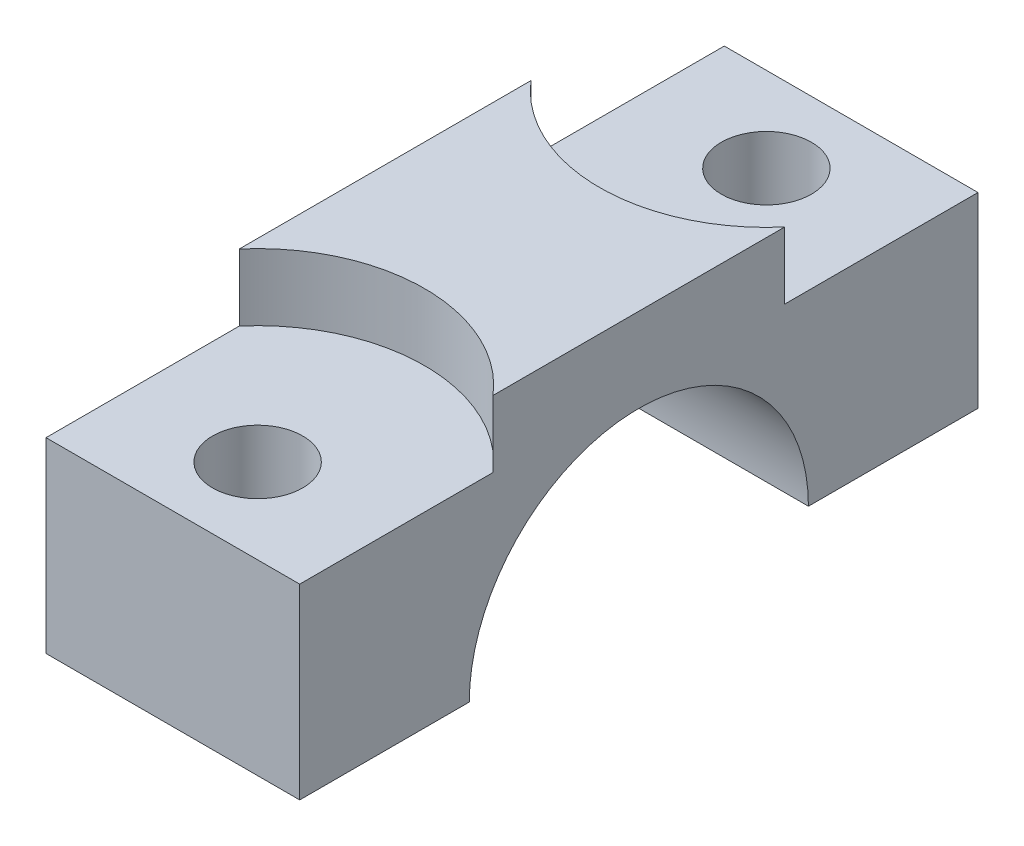
SolidWorks part; units mm, degrees
ref_plane "Front Plane" through (0, 0, 0) normal (0, 0, 1) x (1, 0, 0)
ref_plane "Top Plane" through (0, 0, 0) normal (0, 1, 0) x (1, 0, 0)
ref_plane "Right Plane" through (0, 0, 0) normal (1, 0, 0) x (0, 0, -1)
sketch "Sketch1" plane through (0, 0, 0) normal (1, 0, 0) x (0, 0, -1)
  line L0 (12.7, 0) -> (25.4, 0)
  line L1 (-25.4, 19) -> (25.4, 19)
  line L2 (-25.4, 19) -> (-25.4, 0)
  line L3 (-25.4, 0) -> (-12.7, 0)
  line L4 (25.4, 19) -> (25.4, 0)
  arc A0 (-12.7, 0) -> (12.7, 0) centre (0, 0) cw
  point P10 (0, 19)
  dimension "D3" = 12.7
  dimension "D1" = 50.8
  dimension "D2" = 19
extrude "Boss-Extrude1" add sketch "Sketch1" along normal mid plane 19
sketch "Sketch2" plane through (0, 0, 0) normal (0, -1, 0) x (1, 0, 0)
  line L0 (-9.5, 19.05) -> (9.5, 19.05) construction
  line L1 (-9.5, 25.4) -> (-9.5, 12.7) construction
  line L2 (9.5, 25.4) -> (9.5, 12.7) construction
  line L3 (-9.5, -19.05) -> (9.5, -19.05) construction
  line L4 (-9.5, -12.7) -> (-9.5, -25.4) construction
  line L5 (9.5, -12.7) -> (9.5, -25.4) construction
  point P12 (0, 19.05)
  point P13 (0, -19.05)
sketch "Sketch10" plane through (0, 19, 0) normal (0, 1, 0) x (1, 0, 0)
  line L0 (-9.5, 19.05) -> (9.5, 19.05) construction
  line L1 (-9.5, -19.05) -> (9.5, -19.05) construction
  line L2 (-9.5, 19.05) -> (9.5, 19.05)
  line L3 (-9.5, -19.05) -> (9.5, -19.05)
  point P0 (0, -19.05)
  point P2 (0, 19.05)
  point P8 (0, 19.05)
hole_wizard "CBORE for M12 Hex Head Cap Screw3" positions "3DSketch8" profile "Sketch11" counterbore size "M12" standard "ISO" end condition through all
sketch3d "3DSketch8"
  line L0 (-9.5, 19, -19.05) -> (9.5, 19, -19.05) construction
  point P0 (0, 19, -19.05)
  point P4 (-110.2223, 0, -2.3247)
  point P6 (0, 19, 19.05)
sketch "Sketch11" plane through (0, 19, -19.05) normal (1, 0, 0) x (0, 0, 1)
  line L0 (0, 0) -> (0, 19)
  line L1 (0, 19) -> (3.375, 19)
  line L3 (3.375, 19) -> (3.375, 5)
  line L4 (3.375, 5) -> (12.5, 5)
  line L5 (12.5, 5) -> (12.5, 0)
  line L7 (12.5, 0) -> (0, 0)
  line L11 (0, -6.35) -> (0, 107.95) construction
  dimension "Thru Hole Dia." = 6.75
  dimension "Thru Hole Depth" = 19
  dimension "C'Bore Dia." = 25
  dimension "C'Bore Depth" = 5
